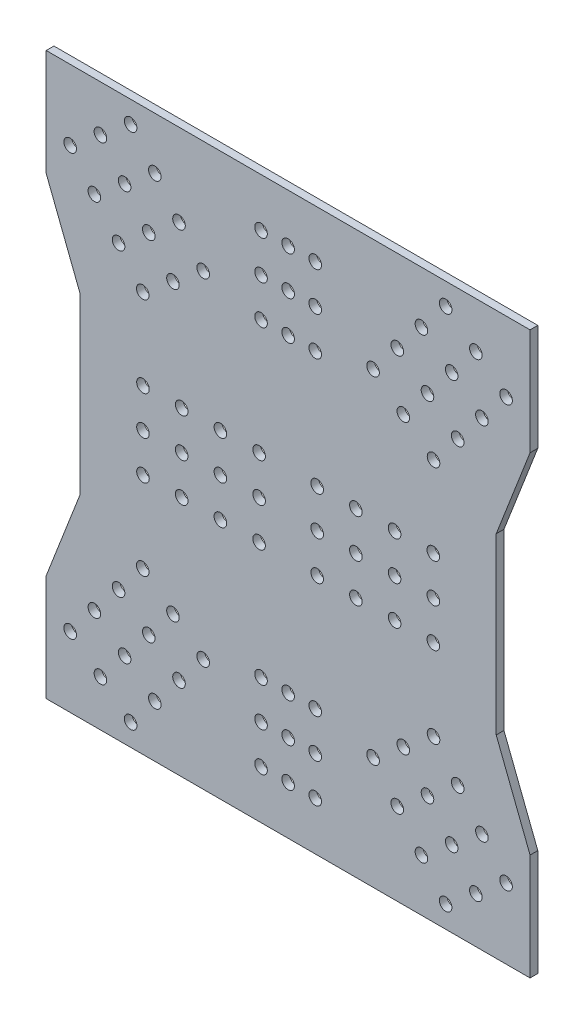
SolidWorks part; units mm, degrees
ref_plane "前视基准面" through (0, 0, 0) normal (0, 0, 1) x (1, 0, 0)
ref_plane "上视基准面" through (0, 0, 0) normal (0, 1, 0) x (1, 0, 0)
ref_plane "右视基准面" through (0, 0, 0) normal (1, 0, 0) x (0, 0, -1)
sketch "草图2" plane through (0, 0, 0) normal (0, 0, 1) x (1, 0, 0)
  line L1 (-500, 580) -> (500, 580)
  line L2 (-500, 580) -> (-500, -580)
  line L3 (-500, -580) -> (500, -580)
  line L4 (500, 580) -> (500, -580)
  dimension "D1" = 1000
  dimension "D2" = 1160
  dimension "D3" = 500
  dimension "D4" = 580
extrude "凸台-拉伸1" add sketch "草图2" along normal blind 16
sketch "草图4" plane through (0, 0, 0) normal (0, 0, -1) x (-1, 0, 0)
  line L0 (-500, -580) -> (-500, 580) construction
  line L1 (-500, 360) -> (-430, 180)
  line L2 (-430, 180) -> (-430, -180)
  line L3 (-430, -180) -> (-500, -360)
  line L4 (-500, -360) -> (-500, 360)
  line L5 (430, 180) -> (430, -180)
  line L6 (430, -180) -> (500, -360)
  line L7 (500, 580) -> (500, -580) construction
  line L8 (500, -360) -> (500, 360)
  line L9 (500, 360) -> (430, 180)
  line L10 (-500, 580) -> (500, 580) construction
  line L11 (500, -580) -> (-500, -580) construction
  dimension "D1" = 70
  dimension "D2" = 70
  dimension "D3" = 220
  dimension "D4" = 180
  dimension "D5" = 220
  dimension "D6" = 180
extrude "切除-拉伸1" cut sketch "草图4" against normal through all
sketch "草图6" plane through (0, 0, 16) normal (0, 0, 1) x (1, 0, 0)
  circle A0 centre (-60, 80) radius 13
  dimension "D1" = 26
  dimension "D2" = 60
  dimension "D3" = 80
extrude "切除-拉伸2" cut sketch "草图6" against normal through all
pattern_linear "阵列(线性)1" count 4 spacing 80 along (-1, 0, 0) count 3 spacing 80 along (0, -1, 0) of "切除-拉伸2"
pattern_linear "阵列(线性)2" count 2 spacing 360 along (1, 0, 0) of "切除-拉伸2", "阵列(线性)1"
sketch "草图7" plane through (0, 0, 16) normal (0, 0, 1) x (1, 0, 0)
  line L0 (500, 580) -> (-500, 580) construction
  circle A0 centre (-56, 480) radius 13
  circle A1 centre (-60, 80) radius 13 construction
  dimension "D1" = 100
  dimension "D2" = 56
extrude "切除-拉伸3" cut sketch "草图7" against normal through all
pattern_linear "阵列(线性)3" count 3 spacing 56 along (1, 0, 0) count 3 spacing 80 along (0, -1, 0) of "切除-拉伸3"
pattern_linear "阵列(线性)4" count 2 spacing 800 along (0, -1, 0) of "切除-拉伸3", "阵列(线性)3"
sketch "草图8" plane through (0, 0, 16) normal (0, 0, 1) x (1, 0, 0)
  line L0 (500, 625) -> (500, 0) construction
  line L1 (489.7468, 740.246) -> (-30745.0055, -38303.1944) construction
  line L2 (825.2368, 903.4835) -> (-30409.5156, -38139.9569) construction
  line L3 (0, 0) -> (500, 0) construction
  line L4 (218.7206, 620.2916) -> (39262.1611, -30614.4608) construction
  line L5 (500, 625) -> (0, 0) construction
  line L6 (-212.5206, 657.9345) -> (38642.4779, -30426.0643) construction
  line L8 (91.4489, 619.6589) -> (39134.8894, -30615.0935) construction
  line L9 (-37.6012, 620.449) -> (39005.8393, -30614.3034) construction
  circle A0 centre (175.5393, 347.4866) radius 13
  circle A1 centre (56, 480) radius 13 construction
  circle A2 centre (300.4783, 247.5354) radius 13
  circle A3 centre (225.5149, 409.9561) radius 13
  circle A4 centre (275.4905, 472.4256) radius 13
  circle A5 centre (325.4661, 534.8951) radius 13
  circle A6 centre (387.9356, 484.9195) radius 13
  circle A7 centre (337.96, 422.45) radius 13
  circle A8 centre (287.9844, 359.9805) radius 13
  circle A9 centre (450.4051, 434.9439) radius 13
  circle A10 centre (400.4295, 372.4744) radius 13
  circle A11 centre (350.4539, 310.0049) radius 13
  circle A12 centre (238.0088, 297.511) radius 13
  dimension "D1" = 500
  dimension "D2" = 625
  dimension "D3" = 80
  dimension "D4" = 381
  dimension "D5" = 80
  dimension "D6" = 80
  dimension "D7" = 80
  dimension "D8" = 80
extrude "切除-拉伸4" cut sketch "草图8" against normal through all
ref_plane "基准面1" through (0, 0, 0) normal (1, 0, 0) x (0, 0, -1)
mirror "镜向1" about plane through (0, 0, 0) normal (1, 0, 0) of "切除-拉伸4"
ref_plane "基准面2" through (0, 0, 0) normal (0, 1, 0) x (1, 0, 0)
mirror "镜向2" about plane through (0, 0, 0) normal (0, 1, 0) of "镜向1", "切除-拉伸4"
